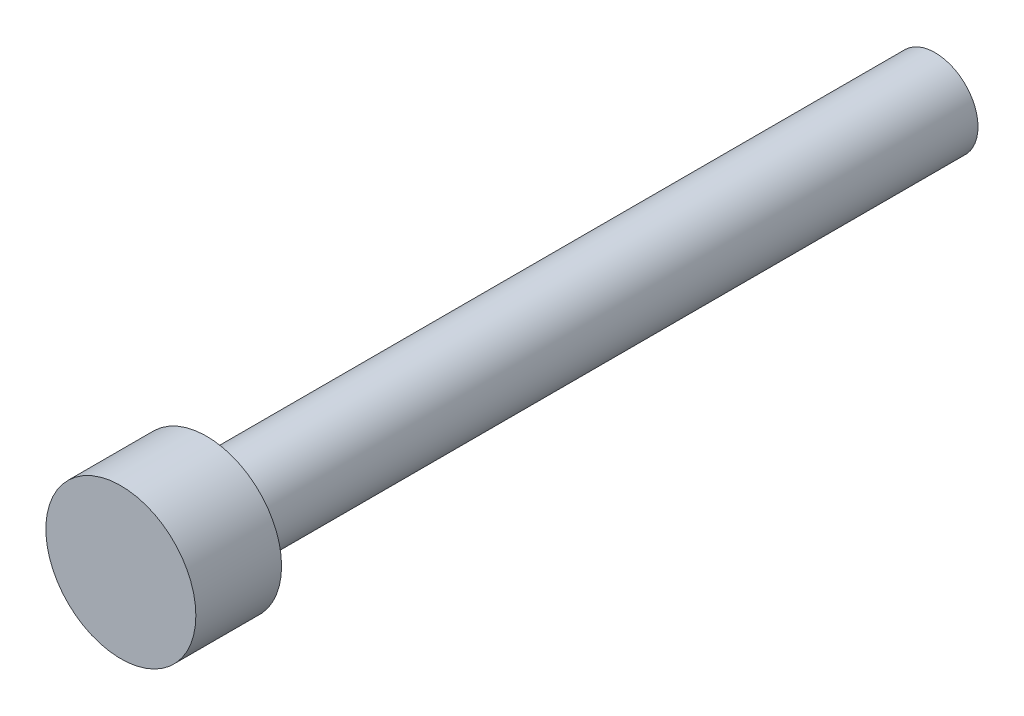
SolidWorks part; units mm, degrees
ref_plane "Plan de face" through (0, 0, 0) normal (0, 0, 1) x (1, 0, 0)
ref_plane "Plan de dessus" through (0, 0, 0) normal (0, 1, 0) x (1, 0, 0)
ref_plane "Plan de droite" through (0, 0, 0) normal (1, 0, 0) x (0, 0, -1)
sketch "Esquisse1" plane through (0, 0, 0) normal (0, 0, 1) x (1, 0, 0)
  circle A0 centre (0, 0) radius 2
  dimension "D1" = 4
extrude "Boss.-Extru.1" add sketch "Esquisse1" along normal blind 34
sketch "Esquisse2" plane through (0, 0, 34) normal (0, 0, 1) x (1, 0, 0)
  circle A0 centre (0, 0) radius 3.5
  dimension "D1" = 7
extrude "Boss.-Extru.2" add sketch "Esquisse2" along normal blind 4 contours A0
